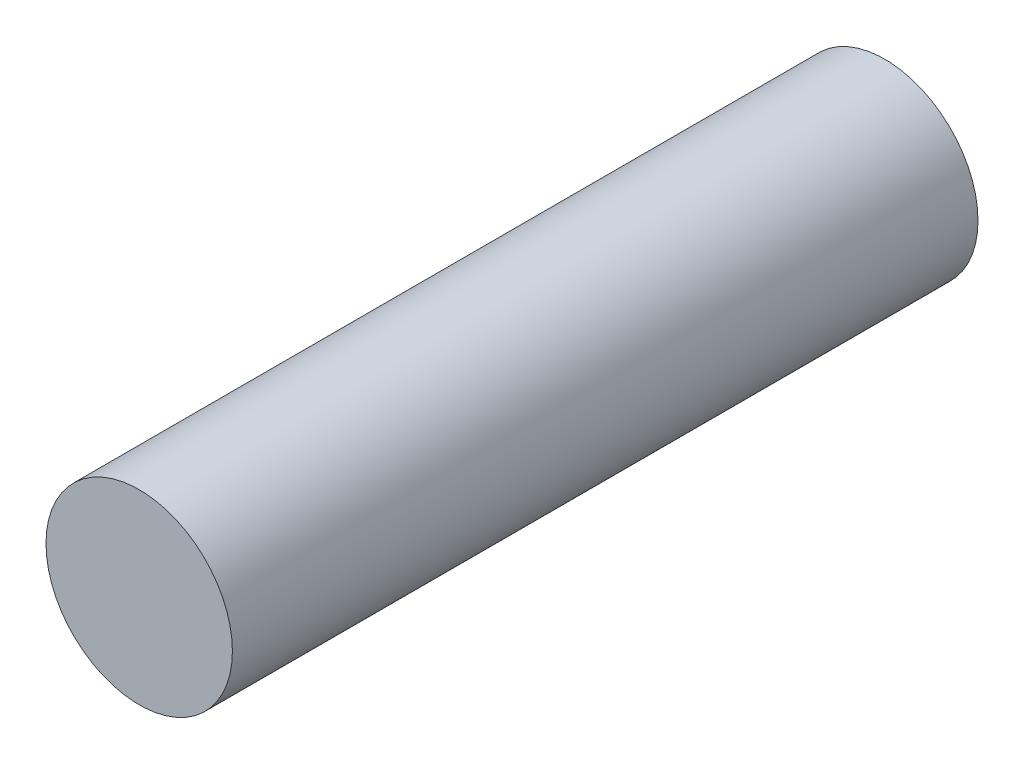
SolidWorks part; units mm, degrees
ref_plane "Front Plane" through (0, 0, 0) normal (0, 0, 1) x (1, 0, 0)
ref_plane "Top Plane" through (0, 0, 0) normal (0, 1, 0) x (1, 0, 0)
ref_plane "Right Plane" through (0, 0, 0) normal (1, 0, 0) x (0, 0, -1)
sketch "Sketch1" plane through (0, 0, 0) normal (0, 0, 1) x (1, 0, 0)
  circle A0 centre (0, 0) radius 3.5
  dimension "D1" = 7
extrude "Boss-Extrude1" add sketch "Sketch1" along normal blind 28
